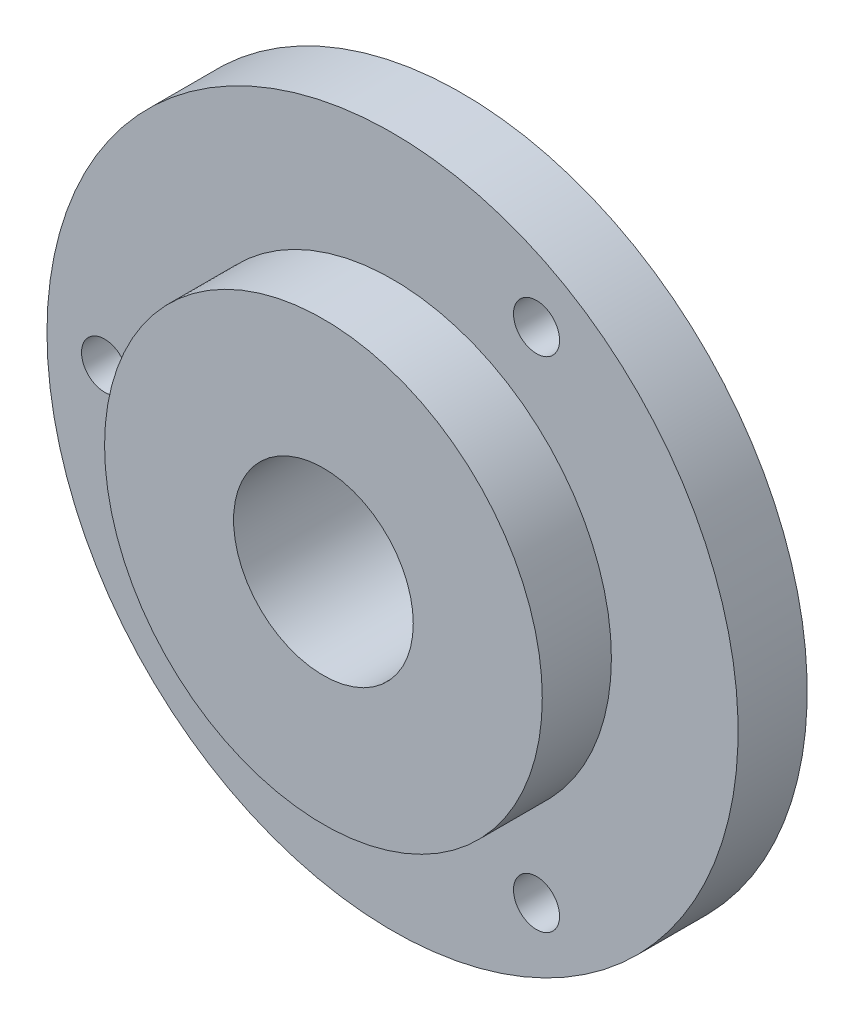
SolidWorks part; units mm, degrees
ref_plane "Спереди" through (0, 0, 0) normal (0, 0, 1) x (1, 0, 0)
ref_plane "Сверху" through (0, 0, 0) normal (0, 1, 0) x (1, 0, 0)
ref_plane "Справа" through (0, 0, 0) normal (1, 0, 0) x (0, 0, -1)
other "Configuration Table"
sketch "Эскиз1" plane through (0, 0, 0) normal (0, 0, 1) x (1, 0, 0)
  circle A0 centre (0, 0) radius 9.5
extrude "Бобышка-Вытянуть1" add sketch "Эскиз1" along normal blind 3
sketch "Эскиз2" plane through (0, 0, 0) normal (0, 0, -1) x (-1, 0, 0)
  circle A0 centre (0, 0) radius 15
extrude "Бобышка-Вытянуть2" add sketch "Эскиз2" along normal blind 3
sketch "Эскиз3" plane through (0, 0, 3) normal (0, 0, 1) x (1, 0, 0)
  circle A0 centre (0, 0) radius 3.9
extrude "Вырез-Вытянуть3" cut sketch "Эскиз3" against normal through all
sketch "Эскиз4" plane through (0, 0, 0) normal (0, 0, 1) x (1, 0, 0)
  line L0 (0, 0) -> (-25.0883, 0) construction
  line L1 (-9.5, 0) -> (-9.5, 10.8301) construction
  line L2 (-12.5, 0) -> (-12.5, 10.8301) construction
  circle A0 centre (0, 0) radius 9.5 construction
  circle A1 centre (-12.5, 0) radius 1
  dimension "D1" = 3
extrude "Вырез-Вытянуть4" cut sketch "Эскиз4" against normal through all
pattern_circular "Круговой массив1" count 3 over 360 about axis through (0, 0, 0) along (0, 0, 1) of "Вырез-Вытянуть4"
